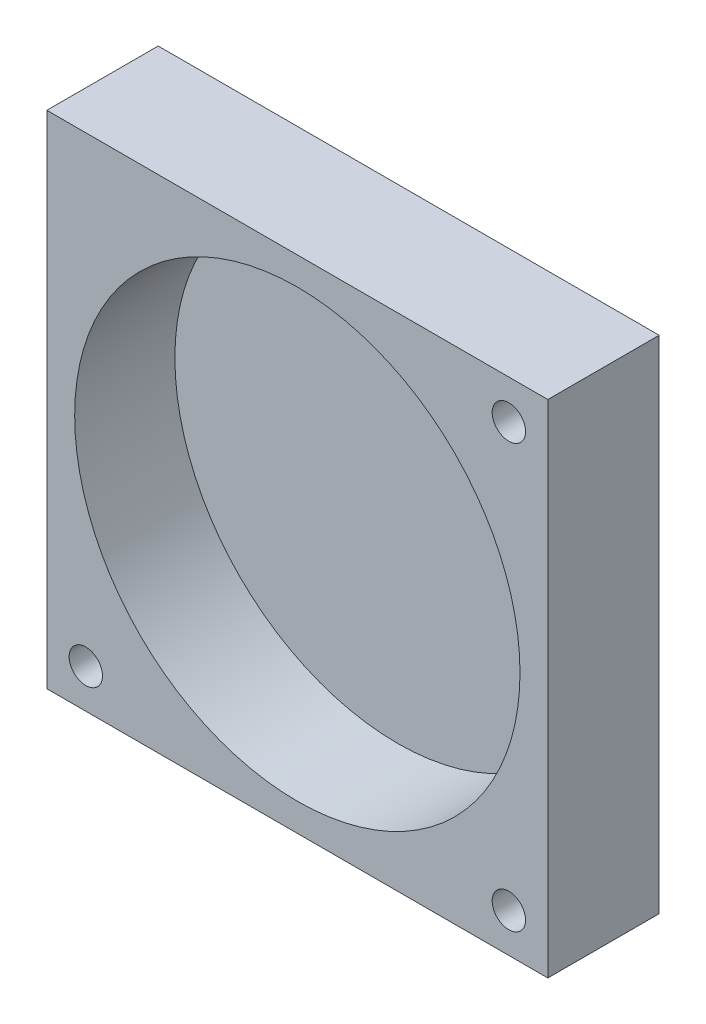
SolidWorks part; units mm, degrees
ref_plane "前基準面" through (0, 0, 0) normal (0, 0, 1) x (1, 0, 0)
ref_plane "上基準面" through (0, 0, 0) normal (0, 1, 0) x (1, 0, 0)
ref_plane "右基準面" through (0, 0, 0) normal (1, 0, 0) x (0, 0, -1)
sketch "草圖1" plane through (0, 0, 0) normal (0, 0, 1) x (1, 0, 0)
  line L1 (-22.5, 22.5) -> (22.5, 22.5)
  line L2 (-22.5, 22.5) -> (-22.5, -22.5)
  line L3 (-22.5, -22.5) -> (22.5, -22.5)
  line L4 (22.5, 22.5) -> (22.5, -22.5)
  circle A0 centre (19, 19) radius 1.5
  circle A1 centre (19, -19) radius 1.5
  circle A2 centre (-19, -19) radius 1.5
  circle A3 centre (0, 0) radius 20
  point P4 (0, 22.5)
  point P6 (22.5, 0)
  dimension "D3" = 3
  dimension "D4" = 3
  dimension "D5" = 3
  dimension "D14" = 40
  dimension "D1" = 45
  dimension "D2" = 45
  dimension "D6" = 38
  dimension "D7" = 38
  dimension "D8" = 3.5
  dimension "D9" = 3.5
  dimension "D10" = 3.5
  dimension "D11" = 3.5
  dimension "D12" = 3.5
  dimension "D13" = 3.5
extrude "填料-伸長1" add sketch "草圖1" along normal blind 10
sketch "草圖2" plane through (0, 0, 0) normal (0, 0, -1) x (-1, 0, 0)
  circle A0 centre (0, 0) radius 20
extrude "填料-伸長2" add sketch "草圖2" against normal blind 1
